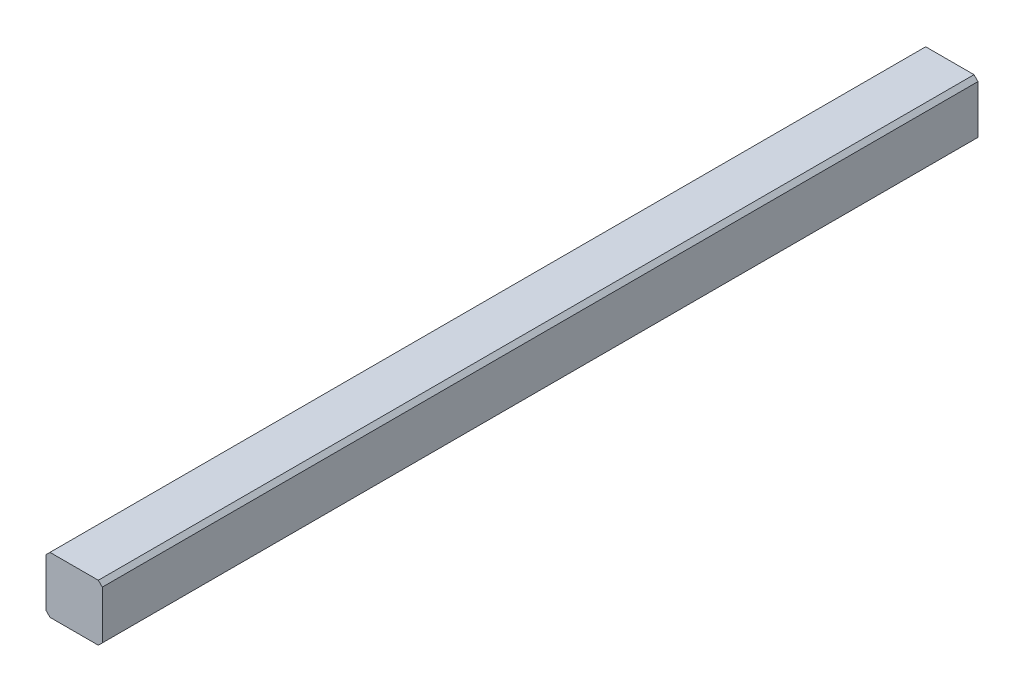
SolidWorks part; units mm, degrees
ref_plane "Front Plane" through (0, 0, 0) normal (0, 0, 1) x (1, 0, 0)
ref_plane "Top Plane" through (0, 0, 0) normal (0, 1, 0) x (1, 0, 0)
ref_plane "Right Plane" through (0, 0, 0) normal (1, 0, 0) x (0, 0, -1)
sketch "Sketch1" plane through (0, 0, 0) normal (0, 0, 1) x (1, 0, 0)
  line L1 (3.5355, -3.5355) -> (-3.5355, -3.5355)
  line L2 (3.5355, -3.5355) -> (3.5355, 3.5355)
  line L3 (3.5355, 3.5355) -> (-3.5355, 3.5355)
  line L4 (-3.5355, -3.5355) -> (-3.5355, 3.5355)
  line L5 (3.5355, -3.5355) -> (-3.5355, 3.5355) construction
  line L6 (3.5355, 3.5355) -> (-3.5355, -3.5355) construction
  circle A0 centre (0, 0) radius 5 construction
  dimension "D1" = 10
extrude "Boss-Extrude1" add sketch "Sketch1" along normal blind 110
chamfer "Chamfer2" distance 0.5 angle 45 4 edges at (3.5355, -3.5355, 55) (-3.5355, -3.5355, 55) (3.5355, 3.5355, 55) (-3.5355, 3.5355, 55)
